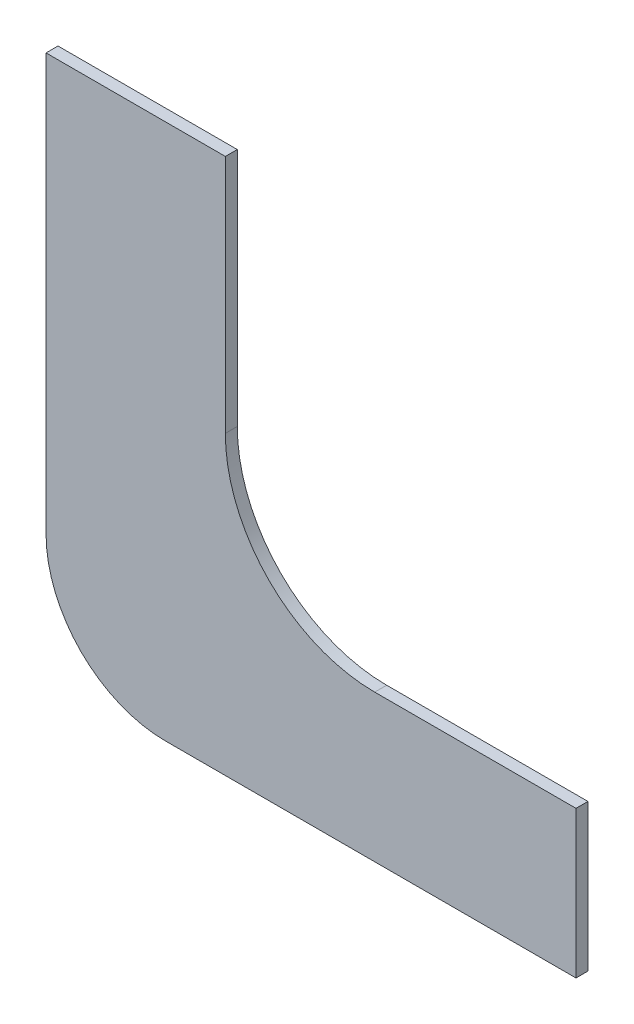
SolidWorks part; units mm, degrees
ref_plane "Front Plane" through (0, 0, 0) normal (0, 0, 1) x (1, 0, 0)
ref_plane "Top Plane" through (0, 0, 0) normal (0, 1, 0) x (1, 0, 0)
ref_plane "Right Plane" through (0, 0, 0) normal (1, 0, 0) x (0, 0, -1)
sketch "Sketch2" plane through (0, 0, 0) normal (0, 0, 1) x (1, 0, 0)
  line L0 (-0.15, 0.35) -> (0.15, 0.35)
  line L1 (0.7368, -0.3014) -> (0.7368, -0.5473)
  line L2 (0.15, -0.5473) -> (0.7368, -0.5473)
  line L3 (-0.15, 0.35) -> (-0.15, -0.3473)
  line L4 (0.05, -0.5473) -> (0.15, -0.5473)
  line L6 (0.15, 0.35) -> (0.15, -0.0514)
  line L7 (0.4, -0.3014) -> (0.7368, -0.3014)
  arc A0 (0.4, -0.3014) -> (0.15, -0.0514) centre (0.4, -0.0514) cw
  arc A1 (0.05, -0.5473) -> (-0.15, -0.3473) centre (0.05, -0.3473) cw
  dimension "D1" = 0.25
  dimension "D2" = 0.2
extrude "Boss-Extrude1" add sketch "Sketch2" along normal mid plane 0.02
